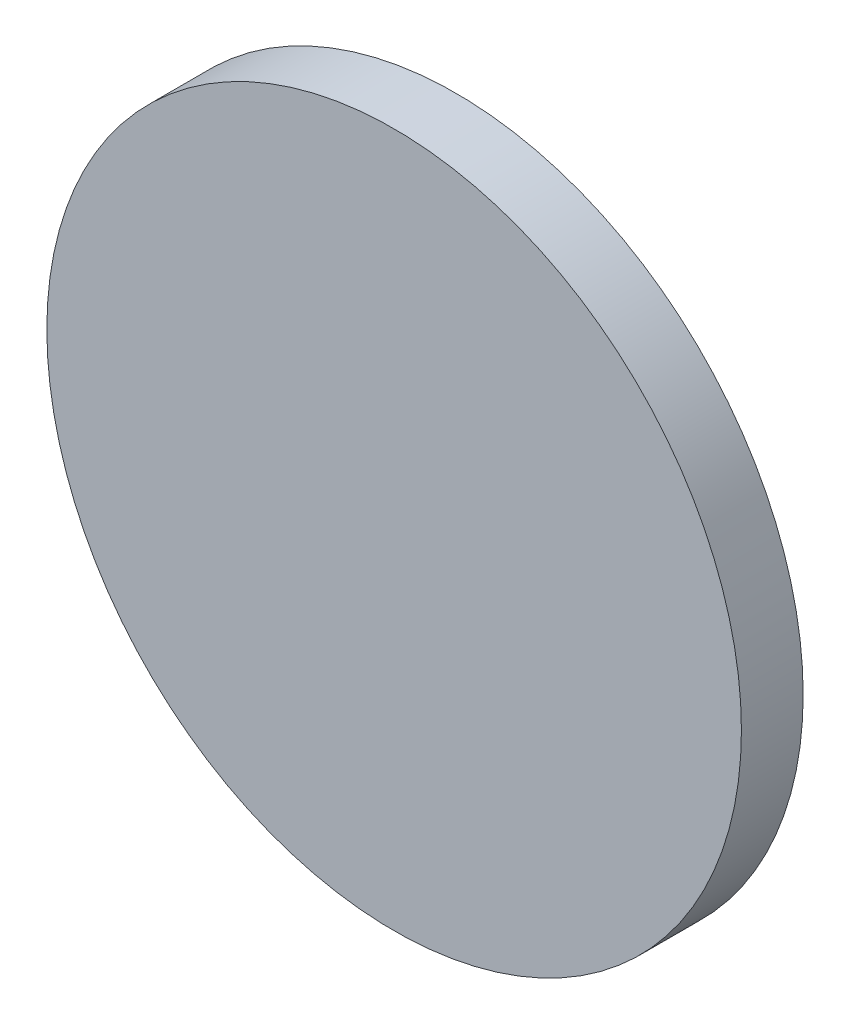
SolidWorks part; units mm, degrees
ref_plane "Front Plane" through (0, 0, 0) normal (0, 0, 1) x (1, 0, 0)
ref_plane "Top Plane" through (0, 0, 0) normal (0, 1, 0) x (1, 0, 0)
ref_plane "Right Plane" through (0, 0, 0) normal (1, 0, 0) x (0, 0, -1)
sketch "Sketch1" plane through (0, 0, 0) normal (0, 0, 1) x (1, 0, 0)
  circle A0 centre (0, 39.7742) radius 11.2507
extrude "Boss-Extrude1" add sketch "Sketch1" along normal blind 2
